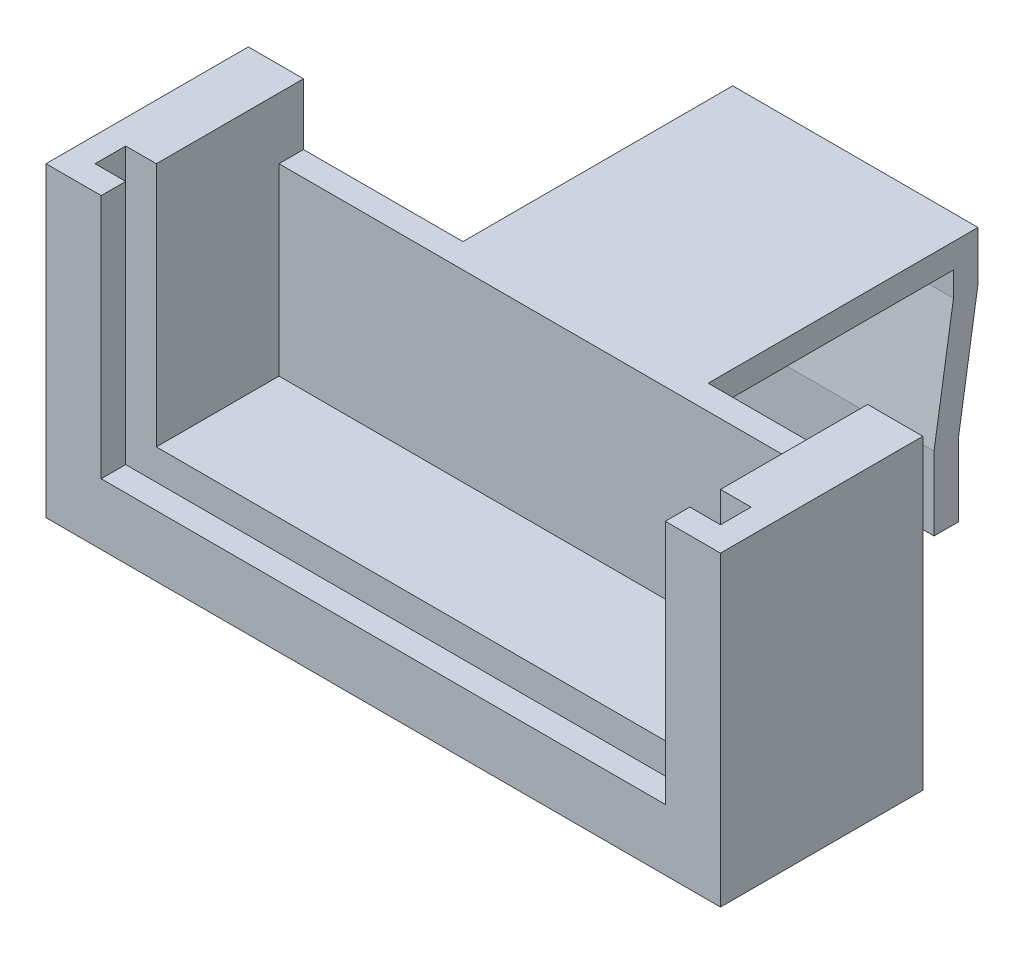
SolidWorks part; units mm, degrees
ref_plane "Front Plane" through (0, 0, 0) normal (0, 0, 1) x (1, 0, 0)
ref_plane "Top Plane" through (0, 0, 0) normal (0, 1, 0) x (1, 0, 0)
ref_plane "Right Plane" through (0, 0, 0) normal (1, 0, 0) x (0, 0, -1)
sketch "Sketch1" plane through (0, 0, 0) normal (0, 0, 1) x (1, 0, 0)
  line L1 (0, 0) -> (55, 0)
  line L2 (0, 0) -> (0, 25)
  line L3 (0, 25) -> (55, 25)
  line L4 (55, 0) -> (55, 25)
  dimension "D1" = 55
  dimension "D2" = 25
extrude "Boss-Extrude1" add sketch "Sketch1" along normal blind 16.5
sketch "Sketch2" plane through (0, 0, 16.5) normal (0, 0, 1) x (1, 0, 0)
  line L2 (4.5, 25) -> (4.5, 5)
  line L3 (4.5, 5) -> (50.5, 5)
  line L4 (0, 25) -> (0, 0) construction
  line L5 (0, 0) -> (55, 0) construction
  line L6 (55, 0) -> (55, 25) construction
  line L7 (55, 25) -> (0, 25) construction
  line L12 (50.5, 25) -> (50.5, 5)
  line L13 (4.5, 25) -> (50.5, 25)
  dimension "D2" = 5
  dimension "D3" = 4.5
  dimension "D1" = 4.5
extrude "Cut-Extrude1" cut sketch "Sketch2" against normal blind 14.5
sketch "Sketch3" plane through (4.5, 0, 0) normal (1, 0, 0) x (0, 0, -1)
  line L0 (-14.5, 5) -> (-14.5, 25)
  line L1 (-16.5, 25) -> (0, 25) construction
  line L2 (-14.5, 25) -> (-12, 25)
  line L3 (-12, 25) -> (-12, 5)
  line L4 (-12, 5) -> (-14.5, 5)
  line L5 (-16.5, 0) -> (-16.5, 25) construction
  line L6 (-16.5, 0) -> (0, 0) construction
  dimension "D1" = 2
  dimension "D2" = 2.5
  dimension "D3" = 5
extrude "Cut-Extrude2" cut sketch "Sketch3" against normal blind 2.5
ref_plane "Plane1" through (27.5, 0, 0) normal (1, 0, 0) x (0, 0, -1)
mirror "Mirror1" about plane through (27.5, 0, 0) normal (1, 0, 0) of "Cut-Extrude2"
sketch "Sketch4" plane through (0, 5, 0) normal (0, 1, 0) x (1, 0, 0)
  line L0 (4.5, -12) -> (50.5, -12)
  line L1 (4.5, -14.5) -> (50.5, -14.5)
  line L12 (4.5, -16.5) -> (50.5, -16.5)
  line L13 (50.5, -16.5) -> (50.5, -14.5)
  line L14 (50.5, -14.5) -> (53, -14.5)
  line L15 (53, -14.5) -> (53, -12)
  line L16 (53, -12) -> (50.5, -12)
  line L17 (50.5, -12) -> (50.5, -2)
  line L18 (50.5, -2) -> (4.5, -2)
  line L19 (4.5, -2) -> (4.5, -12)
  line L20 (4.5, -12) -> (2, -12)
  line L21 (2, -12) -> (2, -14.5)
  line L22 (2, -14.5) -> (4.5, -14.5)
  line L23 (4.5, -14.5) -> (4.5, -16.5)
  line L26 (50.5, -14.5) -> (53, -14.5)
  line L27 (53, -14.5) -> (53, -12)
  line L28 (53, -12) -> (50.5, -12)
  line L32 (4.5, -12) -> (2, -12)
  line L33 (2, -12) -> (2, -14.5)
  line L34 (2, -14.5) -> (4.5, -14.5)
  dimension "D1" = 0
extrude "Cut-Extrude3" cut sketch "Sketch4" against normal blind 3
sketch "Sketch6" plane through (0, 0, 2) normal (0, 0, 1) x (1, 0, 0)
  line L0 (27.5, 25) -> (27.5, 20) construction
  line L1 (50.5, 25) -> (4.5, 25) construction
  line L2 (27.5, 20) -> (4.5, 20)
  line L3 (4.5, 20) -> (4.5, 25)
  line L4 (4.5, 25) -> (50.5, 25)
  line L5 (50.5, 25) -> (50.5, 20)
  line L6 (50.5, 20) -> (27.5, 20)
  line L7 (50.5, 5) -> (50.5, 25) construction
  line L8 (4.5, 25) -> (4.5, 5) construction
  point P4 (27.5, 21.7)
  point P9 (50, 20)
  point P12 (5, 20)
  dimension "D3" = 5
extrude "Cut-Extrude4" cut sketch "Sketch6" against normal through all
sketch "Sketch8" plane through (0, 0, 0) normal (0, 0, -1) x (-1, 0, 0)
  line L1 (-37.5, 18) -> (-17.5, 18)
  line L2 (-37.5, 18) -> (-37.5, 20)
  line L3 (-37.5, 20) -> (-17.5, 20)
  line L4 (-17.5, 18) -> (-17.5, 20)
  line L5 (-27.5, 20) -> (-27.5, 18) construction
  line L6 (0, 0) -> (-55, 0) construction
  line L8 (-27.5, 5.5) -> (-27.5, -5.5) construction
  dimension "D1" = 18
  dimension "D2" = 2
  dimension "D3" = 20
extrude "Boss-Extrude2" add sketch "Sketch8" along normal blind 22
sketch "Sketch9" plane through (0, 18, 0) normal (0, -1, 0) x (1, 0, 0)
  line L0 (37.5, -22) -> (37.5, 0) construction
  line L1 (17.5, -22) -> (37.5, -22)
  line L2 (17.5, -22) -> (17.5, -20)
  line L3 (17.5, -20) -> (37.5, -20)
  line L4 (37.5, -22) -> (37.5, -20)
  dimension "D1" = 2
extrude "Boss-Extrude3" add sketch "Sketch9" along normal blind 2
sketch "Sketch10" plane through (37.5, 0, 0) normal (1, 0, 0) x (0, 0, -1)
  line L0 (20, 16) -> (18.4162, 6)
  line L1 (18.4162, 6) -> (18.4162, 0)
  line L2 (18.4162, 0) -> (20.4162, 0)
  line L3 (20.4162, 0) -> (20.4162, 6)
  line L4 (20.4162, 6) -> (22, 16)
  line L5 (22, 16) -> (20, 16)
  line L6 (22, 16) -> (22, 2.3269) construction
  dimension "D1" = 2
  dimension "D3" = 9
  dimension "D4" = 6
extrude "Boss-Extrude4" add sketch "Sketch10" against normal up to surface (20 mm away) up to face at (17.5, 18, -14)
